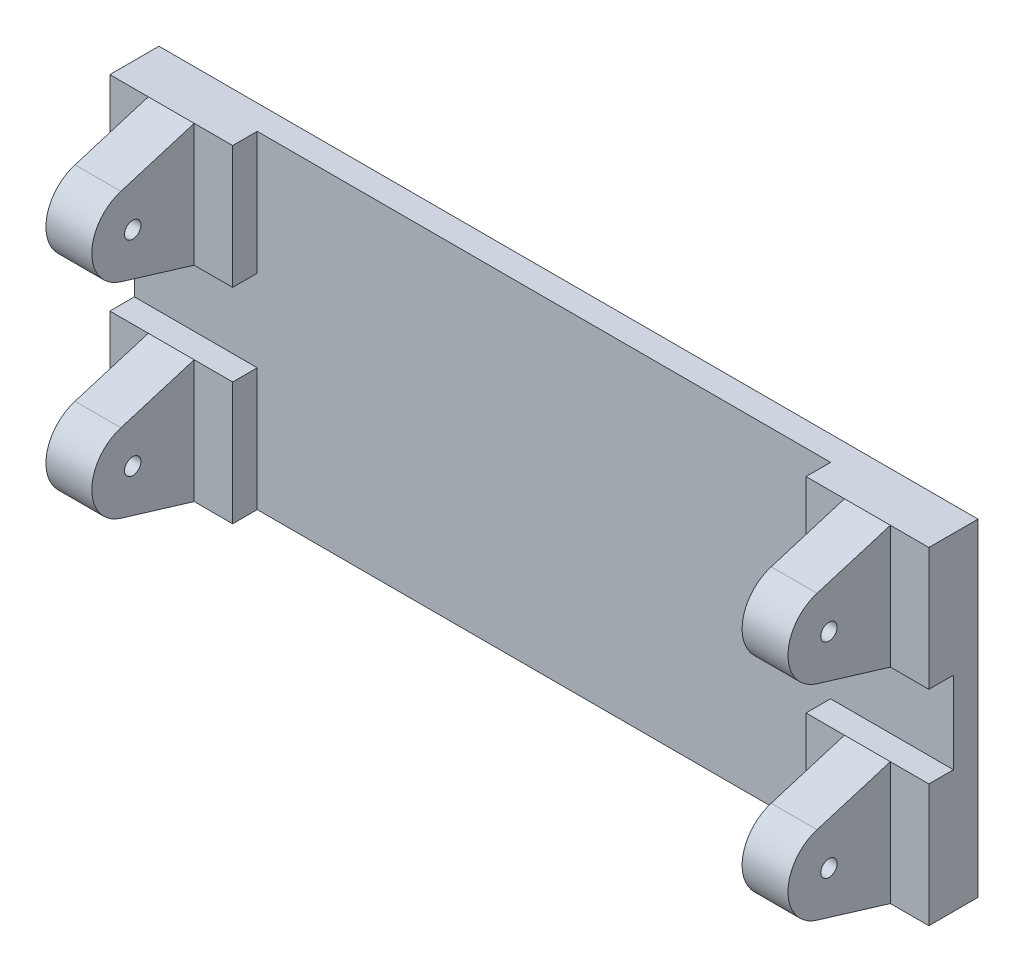
SolidWorks part; units mm, degrees
ref_plane "Front Plane" through (0, 0, 0) normal (0, 0, 1) x (1, 0, 0)
ref_plane "Top Plane" through (0, 0, 0) normal (0, 1, 0) x (1, 0, 0)
ref_plane "Right Plane" through (0, 0, 0) normal (1, 0, 0) x (0, 0, -1)
sketch "Sketch1" plane through (0, 0, 0) normal (0, 0, 1) x (1, 0, 0)
  line L1 (-50, 20) -> (50, 20)
  line L2 (-50, 20) -> (-50, -20)
  line L3 (-50, -20) -> (50, -20)
  line L4 (50, 20) -> (50, -20)
  line L5 (-50, 20) -> (50, -20) construction
  line L6 (-50, -20) -> (50, 20) construction
  point P0 (0, 0)
  dimension "D1" = 40
  dimension "D2" = 100
extrude "Boss-Extrude1" add sketch "Sketch1" along normal blind 3
sketch "Sketch2" plane through (0, 0, 3) normal (0, 0, 1) x (1, 0, 0)
  line L0 (55, 0) -> (-55, 0) construction
  line L1 (-50, 20) -> (-35, 20)
  line L2 (-50, 20) -> (-50, 5)
  line L3 (-50, 5) -> (-35, 5)
  line L4 (-35, 20) -> (-35, 5)
  line L5 (-50, -5) -> (-35, -5)
  line L6 (-35, -20) -> (-35, -5)
  line L7 (-50, -20) -> (-35, -20)
  line L8 (-50, -20) -> (-50, -5)
  line L9 (0, -55) -> (0, 55) construction
  line L10 (50, -20) -> (50, -5)
  line L11 (50, -20) -> (35, -20)
  line L12 (35, -20) -> (35, -5)
  line L13 (50, -5) -> (35, -5)
  line L14 (50, 5) -> (35, 5)
  line L15 (35, 20) -> (35, 5)
  line L16 (50, 20) -> (35, 20)
  line L17 (50, 20) -> (50, 5)
  dimension "D1" = 15
extrude "Boss-Extrude2" add sketch "Sketch2" along normal blind 3
sketch "Sketch3" plane through (-50, 0, 0) normal (-1, 0, 0) x (0, 0, 1)
  line L0 (6, 5) -> (14.9514, 7.7153)
  line L1 (6, 20) -> (14.9514, 17.2847)
  line L2 (6, 20) -> (6, 5)
  arc A0 (14.9514, 7.7153) -> (14.9514, 17.2847) centre (13.5, 12.5) ccw
  circle A1 centre (13.5, 12.5) radius 1
  dimension "D1" = 7.5
  dimension "D2" = 10
  dimension "D3" = 2
extrude "Boss-Extrude3" add sketch "Sketch3" against normal blind 15
sketch "Sketch4" plane through (0, 20, 0) normal (0, 1, 0) x (1, 0, 0)
  line L0 (-35, -6) -> (-50, -6) construction
  line L1 (-39.7, -6) -> (-35, -6)
  line L2 (-39.7, -6) -> (-39.7, -18.5)
  line L3 (-39.7, -18.5) -> (-35, -18.5)
  line L4 (-35, -6) -> (-35, -18.5)
  line L5 (-50, -18.5) -> (-35, -18.5) construction
  line L6 (-50, -6) -> (-45.3, -6)
  line L7 (-50, -6) -> (-50, -18.5)
  line L8 (-50, -18.5) -> (-45.3, -18.5)
  line L9 (-45.3, -6) -> (-45.3, -18.5)
  line L10 (-35, -14.9514) -> (-35, -6) construction
  line L11 (-35, -12.25) -> (-39.7, -12.25) construction
  line L12 (-45.3, -12.25) -> (-50, -12.25) construction
  dimension "D1" = 5.6
extrude "Cut-Extrude1" cut sketch "Sketch4" against normal up to next
mirror "Mirror1" about plane through (0, 0, 0) normal (0, 1, 0) of "Cut-Extrude1", "Boss-Extrude3"
mirror "Mirror2" about plane through (0, 0, 0) normal (1, 0, 0) of "Mirror1", "Boss-Extrude3", "Cut-Extrude1"
